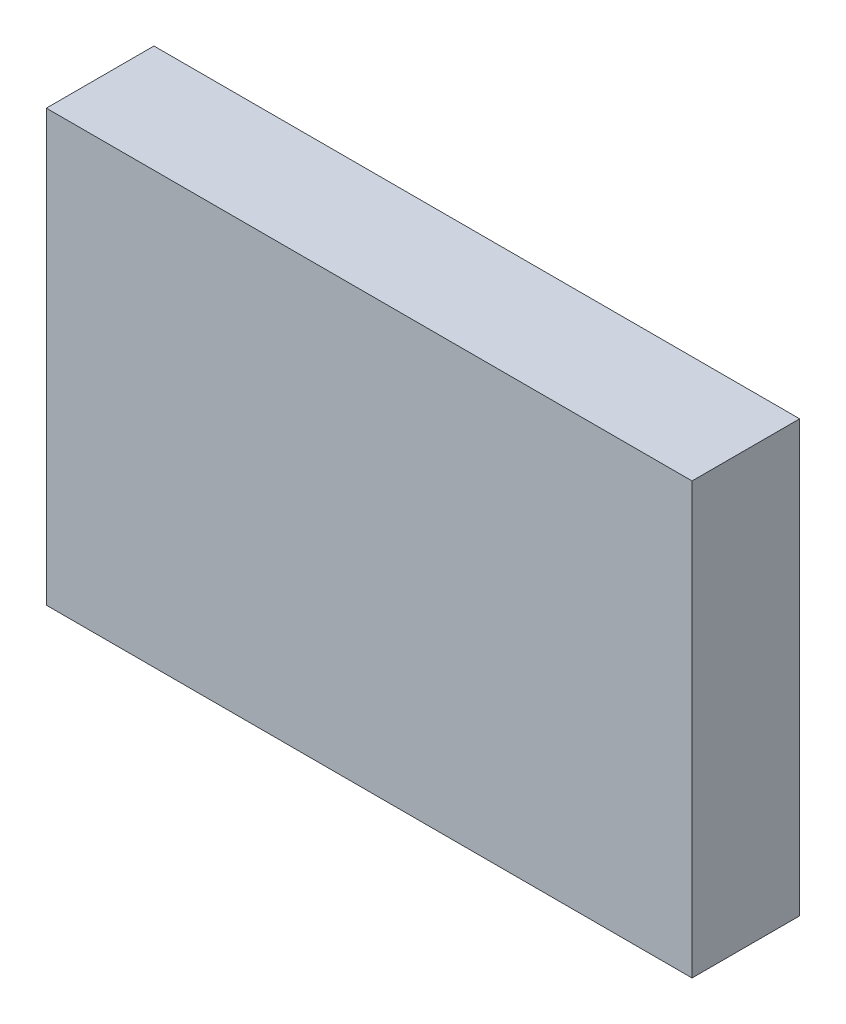
SolidWorks part; units mm, degrees
ref_plane "Přední rovina" through (0, 0, 0) normal (0, 0, 1) x (1, 0, 0)
ref_plane "Horní rovina" through (0, 0, 0) normal (0, 1, 0) x (1, 0, 0)
ref_plane "Pravá rovina" through (0, 0, 0) normal (1, 0, 0) x (0, 0, -1)
ref_plane "Plane2" through (0, 0, 17) normal (0, 0, 1) x (1, 0, 0)
sketch "Sketch3" plane through (0, 0, 17) normal (0, 0, 1) x (1, 0, 0)
  line L1 (15, -10) -> (-15, -10)
  line L2 (15, -10) -> (15, 10)
  line L3 (15, 10) -> (-15, 10)
  line L4 (-15, -10) -> (-15, 10)
  line L5 (15, -10) -> (-15, 10) construction
  line L6 (15, 10) -> (-15, -10) construction
  point P0 (0, 0)
  dimension "D1" = 30
  dimension "D2" = 20
extrude "Boss-Extrude1" add sketch "Sketch3" along normal blind 5
equation "\"SH\" = 3mm"
equation "\"OH\" = 5mm"
equation "\"D1@Boss-Extrude1\"=\"OH\""
